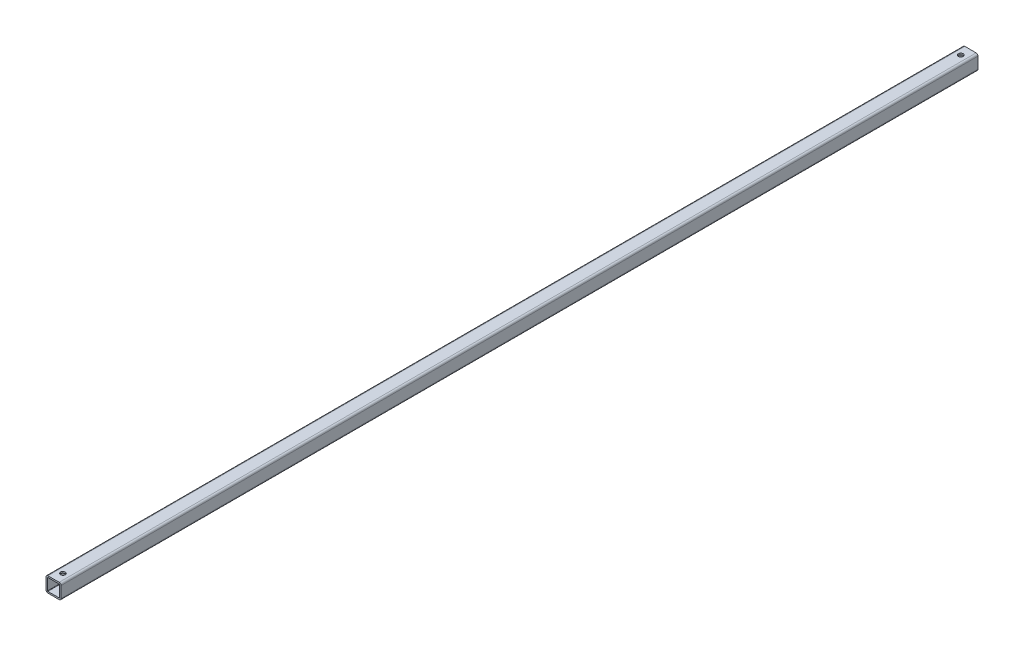
SolidWorks part; units mm, degrees
material "6063-T4"
ref_plane "Front Plane" through (0, 0, 0) normal (0, 0, 1) x (1, 0, 0)
ref_plane "Top Plane" through (0, 0, 0) normal (0, 1, 0) x (1, 0, 0)
ref_plane "Right Plane" through (0, 0, 0) normal (1, 0, 0) x (0, 0, -1)
sketch "Sketch1" plane through (0, 0, 0) normal (0, 0, 1) x (1, 0, 0)
  line L1 (7.5, -10) -> (-7.5, -10)
  line L2 (10, -7.5) -> (10, 7.5)
  line L3 (7.5, 10) -> (-7.5, 10)
  line L4 (-10, -7.5) -> (-10, 7.5)
  line L5 (10, -10) -> (-10, 10) construction
  line L6 (10, 10) -> (-10, -10) construction
  arc A0 (-7.5, 10) -> (-10, 7.5) centre (-7.5, 7.5) ccw
  arc A1 (10, 7.5) -> (7.5, 10) centre (7.5, 7.5) ccw
  arc A2 (7.5, -10) -> (10, -7.5) centre (7.5, -7.5) ccw
  arc A3 (-7.5, -10) -> (-10, -7.5) centre (-7.5, -7.5) cw
  point P0 (0, 0)
  dimension "D2" = 2.5
  dimension "D1" = 20
extrude "Extrude-Thin1" add sketch "Sketch1" along normal mid plane 1219.2 thin
hole_wizard "1/4 (0.25) Diameter Hole1" positions "Sketch4" profile "Sketch5" hole size "1/4" standard "ANSI Inch"
sketch "Sketch4" plane through (0, 10, 0) normal (0, 1, 0) x (1, 0, 0)
  point P0 (-0.2, 596.9)
  point P3 (-0.2, -596.9)
sketch "Sketch5" plane through (-0.2, 10, -596.9) normal (1, 0, 0) x (0, 0, 1)
  line L0 (0, 0) -> (0, 27.3077)
  line L1 (0, 27.3077) -> (3.175, 25.4)
  line L2 (3.175, 25.4) -> (3.175, 0)
  line L5 (3.175, 0) -> (0, 0)
  line L10 (0, 27.3077) -> (-3.175, 25.4) construction
  line L11 (0, -6.35) -> (0, 107.95) construction
  dimension "Hole Dia." = 6.35
  dimension "Hole Depth" = 25.4
  dimension "Drill Angle" = 118
equation "\"D2@Sketch1\" = \"D5@Extrude-Thin1\" * 1.25"
